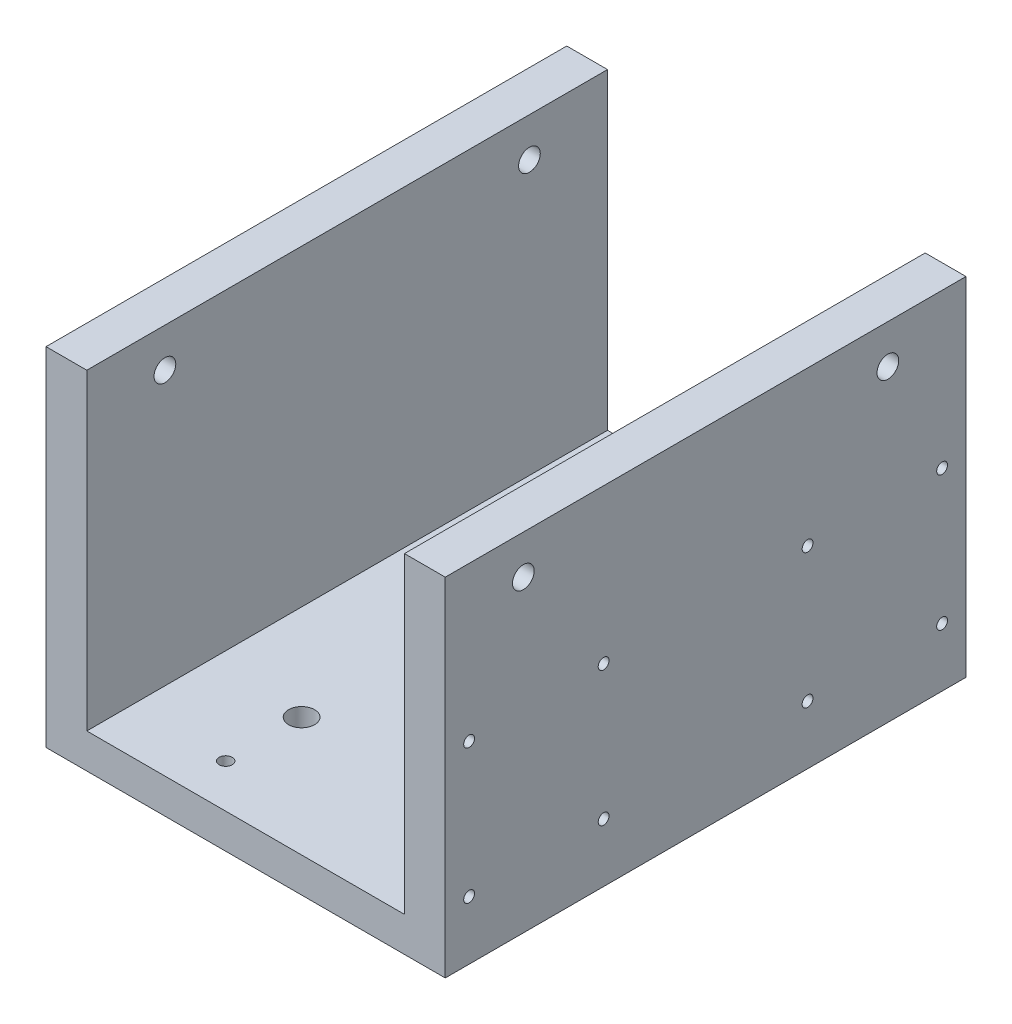
SolidWorks part; units mm, degrees
material "1060 Alloy"
ref_plane "Front Plane" through (0, 0, 0) normal (0, 0, 1) x (1, 0, 0)
ref_plane "Top Plane" through (0, 0, 0) normal (0, 1, 0) x (1, 0, 0)
ref_plane "Right Plane" through (0, 0, 0) normal (1, 0, 0) x (0, 0, -1)
sketch "Sketch1" plane through (0, 0, 0) normal (0, 1, 0) x (1, 0, 0)
  line L1 (0, 0) -> (92, 0)
  line L2 (0, 0) -> (0, 120)
  line L3 (0, 120) -> (92, 120)
  line L4 (92, 0) -> (92, 120)
  dimension "D1" = 120
  dimension "D2" = 92
extrude "Boss-Extrude1" add sketch "Sketch1" along normal blind 8
sketch "Sketch2" plane through (0, 8, 0) normal (0, 1, 0) x (1, 0, 0)
  line L0 (0, 120) -> (9.4, 120)
  line L1 (92, 120) -> (0, 120) construction
  line L2 (9.4, 120) -> (9.4, 0)
  line L3 (0, 0) -> (92, 0) construction
  line L4 (9.4, 0) -> (0, 0)
  line L6 (0, 120) -> (0, 0) construction
  line L18 (0, 0) -> (0, 120)
  line L21 (46, 120) -> (46, 0) construction
  line L39 (82.6, 120) -> (82.6, 0)
  line L40 (92, 120) -> (82.6, 120)
  line L41 (92, 0) -> (92, 120)
  line L42 (82.6, 0) -> (92, 0)
  dimension "D1" = 9.4
extrude "Boss-Extrude2" add sketch "Sketch2" along normal blind 72
sketch "Sketch3" plane through (0, 0, 0) normal (0, -1, 0) x (1, 0, 0)
  line L0 (31.4, 0) -> (31.4, -120) construction
  line L1 (0, 0) -> (92, 0) construction
  line L2 (92, -120) -> (0, -120) construction
  line L3 (92, -92.5) -> (0, -92.5) construction
  line L4 (92, 0) -> (92, -120) construction
  line L5 (0, -120) -> (0, 0) construction
  line L6 (0, -60) -> (92, -60) construction
  circle A0 centre (31.4, -92.5) radius 3
  circle A1 centre (31.4, -110) radius 1.5
  circle A4 centre (31.4, -10) radius 1.5
  circle A5 centre (31.4, -27.5) radius 3
  dimension "D2" = 6
  dimension "D5" = 3
  dimension "D1" = 27.5
  dimension "D3" = 31.4
  dimension "D4" = 17.5
extrude "Cut-Extrude1" cut sketch "Sketch3" against normal up to next
sketch "Sketch4" plane through (92, 0, 0) normal (1, 0, 0) x (0, 0, -1)
  line L0 (60, 80) -> (60, 0) construction
  line L1 (0, 80) -> (120, 80) construction
  line L2 (0, 0) -> (120, 0) construction
  line L3 (0, 80) -> (0, 0) construction
  line L4 (120, 8) -> (0, 8) construction
  circle A0 centre (5.5, 44.5) radius 1.25
  circle A1 centre (36.5, 44.5) radius 1.25
  circle A2 centre (5.5, 13.5) radius 1.25
  circle A3 centre (36.5, 13.5) radius 1.25
  circle A4 centre (83.5, 13.5) radius 1.25
  circle A5 centre (114.5, 13.5) radius 1.25
  circle A6 centre (83.5, 44.5) radius 1.25
  circle A7 centre (114.5, 44.5) radius 1.25
  dimension "D1" = 2.5
  dimension "D2" = 31
  dimension "D5" = 5.5
  dimension "D3" = 31
  dimension "D4" = 5.5
extrude "Cut-Extrude2" cut sketch "Sketch4" against normal up to next
sketch "Sketch5" plane through (92, 0, 0) normal (1, 0, 0) x (0, 0, -1)
  line L0 (120, 80) -> (120, 0) construction
  line L1 (0, 80) -> (0, 0) construction
  line L2 (0, 80) -> (120, 80) construction
  circle A0 centre (18, 71) radius 2.5
  circle A1 centre (102, 71) radius 2.5
  point P4 (0, 0)
  dimension "D4" = 5
  dimension "D1" = 18
  dimension "D2" = 18
  dimension "D3" = 9
extrude "Cut-Extrude3" cut sketch "Sketch5" against normal through all
